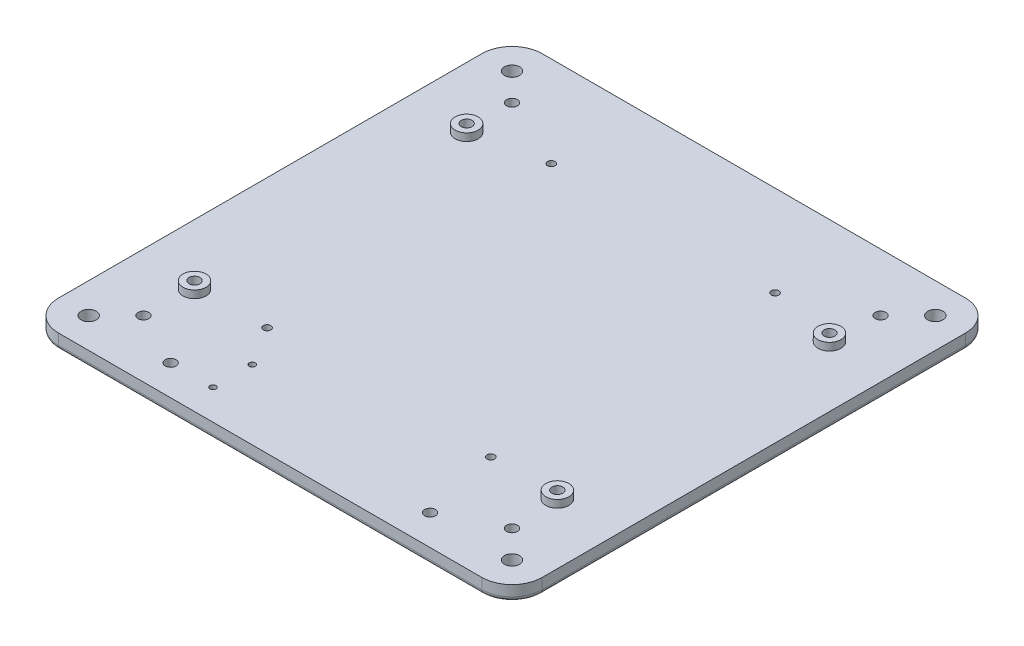
SolidWorks part; units mm, degrees
ref_plane "Front Plane" through (0, 0, 0) normal (0, 0, 1) x (1, 0, 0)
ref_plane "Top Plane" through (0, 0, 0) normal (0, 1, 0) x (1, 0, 0)
ref_plane "Right Plane" through (0, 0, 0) normal (1, 0, 0) x (0, 0, -1)
sketch "Sketch1" plane through (0, 0, 0) normal (0, 1, 0) x (1, 0, 0)
  line L1 (0, 0) -> (203.2, 0)
  line L2 (0, 0) -> (0, 203.2)
  line L3 (0, 203.2) -> (203.2, 203.2)
  line L4 (203.2, 0) -> (203.2, 203.2)
  dimension "D1" = 203.2
  dimension "D2" = 203.2
extrude "Boss-Extrude1" add sketch "Sketch1" along normal blind 6.35
fillet "Fillet1" radius 12.7 4 edges at (0, 3.175, -203.2) (0, 3.175, 0) (203.2, 3.175, 0) (203.2, 3.175, -203.2)
sketch "Sketch2" plane through (0, 0, 0) normal (0, -1, 0) x (1, 0, 0)
  circle A0 centre (12.7, -12.7) radius 3.175
  circle A1 centre (190.5, -12.7) radius 3.175
  circle A2 centre (190.5, -190.5) radius 3.175
  circle A3 centre (12.7, -190.5) radius 3.175
  arc A4 (190.5, -203.2) -> (203.2, -190.5) centre (190.5, -190.5) ccw construction
  arc A5 (12.7, 0) -> (0, -12.7) centre (12.7, -12.7) ccw construction
  arc A6 (12.7, 0) -> (0, -12.7) centre (12.7, -12.7) ccw construction
  dimension "D1" = 6.35
  dimension "D2" = 9.525
extrude "Cut-Extrude1" cut sketch "Sketch2" against normal through all
fillet "Fillet2" radius 1.905 12 edges at (3.7197, 0, -3.7197) (101.6, 0, 0) (199.4803, 0, -3.7197) (203.2, 0, -101.6) (199.4803, 0, -199.4803) (101.6, 0, -203.2) (3.7197, 0, -199.4803) (0, 0, -101.6) (12.7, 0, -15.875) (190.5, 0, -15.875) (190.5, 0, -193.675) (12.7, 0, -193.675)
sketch "Sketch3" plane through (0, 6.35, 0) normal (0, 1, 0) x (1, 0, 0)
  line L0 (3.7197, 3.7197) -> (24.1978, 24.1978) construction
  line L1 (24.1978, 24.1978) -> (0, 24.1978) construction
  line L2 (0, 190.5) -> (0, 12.7) construction
  line L3 (24.1978, 24.1978) -> (24.1978, 0) construction
  line L4 (12.7, 0) -> (190.5, 0) construction
  line L5 (3.7197, 199.4803) -> (24.1978, 179.0022) construction
  line L6 (0, 179.0022) -> (24.1978, 179.0022) construction
  line L7 (24.1978, 179.0022) -> (24.1978, 203.2) construction
  line L8 (190.5, 203.2) -> (12.7, 203.2) construction
  line L9 (199.4803, 3.7197) -> (179.0022, 24.1978) construction
  line L10 (179.0022, 24.1978) -> (179.0022, 0) construction
  line L12 (179.0022, 24.1978) -> (203.2, 24.1978) construction
  line L13 (203.2, 12.7) -> (203.2, 190.5) construction
  line L14 (199.4803, 199.4803) -> (179.0022, 179.0022) construction
  line L15 (179.0022, 179.0022) -> (203.2, 179.0022) construction
  line L16 (179.0022, 179.0022) -> (179.0022, 203.2) construction
  arc A0 (0, 12.7) -> (12.7, 0) centre (12.7, 12.7) ccw construction
  circle A1 centre (24.1978, 24.1978) radius 2.286
  arc A2 (190.5, 0) -> (203.2, 12.7) centre (190.5, 12.7) ccw construction
  arc A3 (203.2, 190.5) -> (190.5, 203.2) centre (190.5, 190.5) ccw construction
  arc A10 (12.7, 203.2) -> (0, 190.5) centre (12.7, 190.5) ccw construction
  circle A13 centre (179.0022, 179.0022) radius 2.286
  circle A14 centre (179.0022, 24.1978) radius 2.286
  circle A15 centre (24.1978, 179.0022) radius 2.286
  point P20 (101.6, 101.6)
  dimension "D2" = 4.572
  dimension "D1" = 28.9603
extrude "Cut-Extrude2" cut sketch "Sketch3" against normal through all
sketch "Sketch4" plane through (0, 6.35, 0) normal (0, 1, 0) x (1, 0, 0)
  line L0 (0, 190.5) -> (0, 12.7) construction
  line L1 (203.2, 12.7) -> (203.2, 190.5) construction
  line L2 (12.7, 0) -> (190.5, 0) construction
  circle A0 centre (47.117, 12.7) radius 2.286
  circle A1 centre (156.083, 12.7) radius 2.286
  dimension "D4" = 4.572
  dimension "D1" = 47.117
  dimension "D2" = 47.117
  dimension "D3" = 12.7
extrude "Cut-Extrude3" cut sketch "Sketch4" against normal through all
sketch "Sketch5" plane through (0, 6.35, 0) normal (0, 1, 0) x (1, 0, 0)
  line L0 (0, 190.5) -> (0, 12.7) construction
  line L1 (203.2, 12.7) -> (203.2, 190.5) construction
  line L2 (12.7, 0) -> (190.5, 0) construction
  line L3 (190.5, 203.2) -> (12.7, 203.2) construction
  circle A0 centre (25.4, 158.75) radius 2.286
  circle A1 centre (177.8, 158.75) radius 2.286
  circle A2 centre (177.8, 44.45) radius 2.286
  circle A3 centre (25.4, 44.45) radius 2.286
  circle A4 centre (25.4, 158.75) radius 4.826
  circle A5 centre (177.8, 158.75) radius 4.826
  circle A6 centre (177.8, 44.45) radius 4.826
  circle A7 centre (25.4, 44.45) radius 4.826
  dimension "D1" = 2.54
  dimension "D2" = 4.572
  dimension "D3" = 25.4
  dimension "D4" = 25.4
  dimension "D5" = 44.45
  dimension "D6" = 44.45
extrude "Boss-Extrude2" add sketch "Sketch5" along normal blind 3.175
sketch "Sketch6" plane through (0, 6.35, 0) normal (0, 1, 0) x (1, 0, 0)
  line L0 (62.357, 10.16) -> (90.297, 10.16) construction
  line L1 (90.297, 10.16) -> (90.297, 31.75) construction
  line L2 (90.297, 31.75) -> (62.357, 31.75) construction
  line L3 (62.357, 31.75) -> (62.357, 10.16) construction
  line L4 (12.7, 0) -> (190.5, 0) construction
  line L5 (64.897, 12.7) -> (64.897, 29.21) construction
  circle A0 centre (64.897, 29.21) radius 1.27
  circle A1 centre (64.897, 12.7) radius 1.27
  circle A2 centre (47.117, 12.7) radius 2.286 construction
  point P10 (64.897, 20.955)
  point P11 (62.357, 20.955)
  dimension "D5" = 2.54
  dimension "D1" = 21.59
  dimension "D2" = 27.94
  dimension "D3" = 10.16
  dimension "D4" = 16.51
  dimension "D6" = 2.54
  dimension "D7" = 15.24
extrude "Cut-Extrude4" cut sketch "Sketch6" against normal through all
sketch "Sketch7" plane through (0, 6.35, 0) normal (0, 1, 0) x (1, 0, 0)
  line L0 (50.8, 168.91) -> (50.8, 41.91) construction
  line L1 (50.8, 41.91) -> (152.4, 41.91) construction
  line L2 (152.4, 41.91) -> (152.4, 168.91) construction
  line L3 (152.4, 168.91) -> (50.8, 168.91) construction
  line L5 (190.5, 203.2) -> (12.7, 203.2) construction
  circle A0 centre (64.897, 29.21) radius 1.27 construction
  circle A1 centre (54.61, 45.72) radius 1.5875
  circle A2 centre (54.61, 165.1) radius 1.5875
  circle A3 centre (148.59, 165.1) radius 1.5875
  circle A4 centre (148.59, 45.72) radius 1.5875
  point P6 (101.6, 168.91)
  point P9 (101.6, 203.2)
  point P18 (0, 0)
  point P19 (0, 0)
  point P20 (0, 0)
  point P21 (0, 0)
  point P22 (0, 0)
  dimension "D5" = 3.175
  dimension "D1" = 127
  dimension "D2" = 101.6
  dimension "D3" = 12.7
  dimension "D4" = 3.81
  dimension "D6" = 3.81
  dimension "D7" = 3.81
  dimension "D8" = 3.81
extrude "Cut-Extrude5" cut sketch "Sketch7" against normal through all
